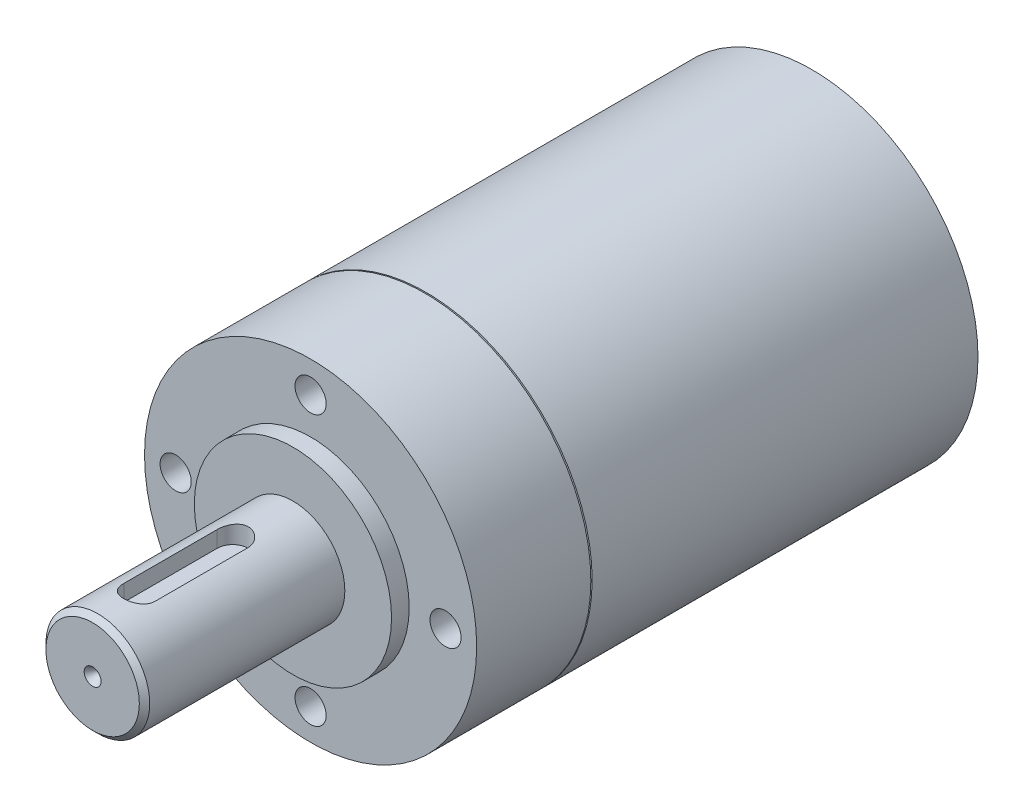
SolidWorks part; units mm, degrees
material "AISI 1020"
ref_plane "前视基准面" through (0, 0, 0) normal (0, 0, 1) x (1, 0, 0)
ref_plane "上视基准面" through (0, 0, 0) normal (0, 1, 0) x (1, 0, 0)
ref_plane "右视基准面" through (0, 0, 0) normal (1, 0, 0) x (0, 0, -1)
sketch "草图8" plane through (0, 0, 0) normal (0, 0, 1) x (1, 0, 0)
  circle A0 centre (0, 0) radius 16
extrude "凸台-拉伸1" add sketch "草图8" along normal blind 48.3
sketch "草图9" plane through (0, 0, 48.3) normal (0, 0, 1) x (1, 0, 0)
  circle A0 centre (0, 0) radius 9.5
extrude "凸台-拉伸2" add sketch "草图9" along normal blind 1.7
sketch "草图10" plane through (0, 0, 50) normal (0, 0, 1) x (1, 0, 0)
  circle A0 centre (0, 0) radius 5
extrude "凸台-拉伸3" add sketch "草图10" along normal blind 19.3
sketch "草图11" plane through (0, 0, 69.3) normal (0, 0, 1) x (1, 0, 0)
  circle A0 centre (0, 0) radius 0.8133
extrude "切除-拉伸7" cut sketch "草图11" against normal blind 3 draft 32
ref_plane "基准面5" through (0, 3.2, 0) normal (0, 1, 0) x (1, 0, 0)
sketch "草图12" plane through (0, 3.2, 0) normal (0, 1, 0) x (1, 0, 0)
  line L0 (0, -69.3) -> (0, -64.8) construction
  line L1 (-5, -69.3) -> (5, -69.3) construction
  line L2 (0, -64.8) -> (0, -55.8) construction
  line L3 (-1.5, -64.8) -> (-1.5, -55.8)
  line L4 (1.5, -64.8) -> (1.5, -55.8)
  arc A0 (-1.5, -64.8) -> (1.5, -64.8) centre (0, -64.8) ccw
  arc A1 (1.5, -55.8) -> (-1.5, -55.8) centre (0, -55.8) ccw
  point P5 (0, -60.3)
  dimension "D1" = 4.5
  dimension "D2" = 1.5
  dimension "D3" = 9
extrude "切除-拉伸8" cut sketch "草图12" along normal blind 3
sketch "草图13" plane through (0, 0, 48.3) normal (0, 0, 1) x (1, 0, 0)
  circle A0 centre (0, 0) radius 13 construction
  circle A1 centre (0, 13) radius 1.5
  circle A2 centre (-13, 0) radius 1.5
  circle A3 centre (0, -13) radius 1.5
  circle A4 centre (13, 0) radius 1.5
  dimension "D1" = 26
  dimension "D2" = 3
extrude "切除-拉伸9" cut sketch "草图13" against normal blind 6
sketch "草图14" plane through (0, 0, 0) normal (0, 0, -1) x (-1, 0, 0)
  circle A0 centre (0, 0) radius 8
extrude "切除-拉伸10" cut sketch "草图14" against normal blind 1.2
sketch "草图15" plane through (0, 0, 0) normal (0, 0, -1) x (-1, 0, 0)
  circle A0 centre (0, 0) radius 2.5
extrude "切除-拉伸11" cut sketch "草图15" against normal blind 20
sketch "草图16" plane through (0, 0, 0) normal (0, 0, -1) x (-1, 0, 0)
  circle A0 centre (0, 0) radius 11 construction
  circle A1 centre (0, 11) radius 1.5
  circle A2 centre (11, 0) radius 1.5
  circle A3 centre (0, -11) radius 1.5
  circle A4 centre (-11, 0) radius 1.5
extrude "切除-拉伸12" cut sketch "草图16" against normal blind 4
sketch "草图17" plane through (0, 0, 0) normal (0, 1, 0) x (1, 0, 0)
  line L0 (-16, -48.3) -> (16, -48.3) construction
  line L1 (17.2076, -37.3) -> (15.8202, -37.3)
  line L2 (17.2076, -37.3) -> (17.2076, -37.1732)
  line L3 (17.2076, -37.1732) -> (15.8202, -37.1732)
  line L4 (15.8202, -37.3) -> (15.8202, -37.1732)
  dimension "D1" = 11
revolve "切除-旋转1" cut sketch "草图17" angle 360 about axis through (0, 0, 69.3) along (0, 0, -1)
chamfer "倒角1" distance 0.5 angle 45 1 edges at (5, 0, 69.3)
move or copy body "实体-移动/复制1" [suppressed] bodies to move or copy 117
